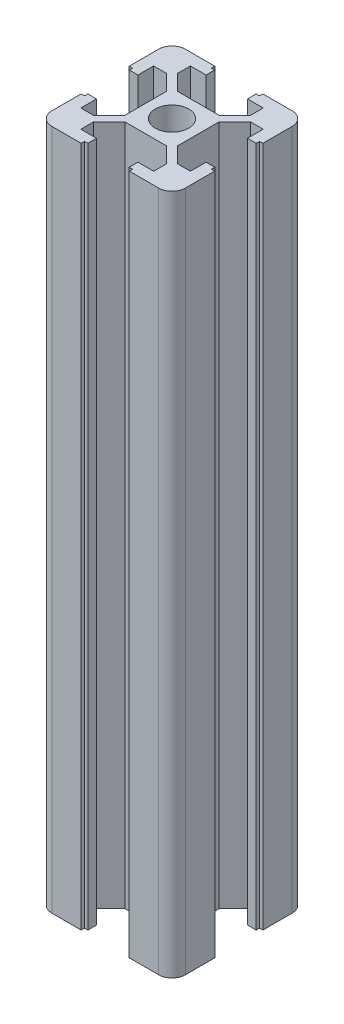
SolidWorks part; units mm, degrees
ref_plane "前视基准面" through (0, 0, 0) normal (0, 0, 1) x (1, 0, 0)
ref_plane "上视基准面" through (0, 0, 0) normal (0, 1, 0) x (1, 0, 0)
ref_plane "右视基准面" through (0, 0, 0) normal (1, 0, 0) x (0, 0, -1)
sketch "草图1" plane through (0, 0, 0) normal (0, 1, 0) x (1, 0, 0)
  line L0 (-6.2985, -5.45) -> (-3.9485, -3.1)
  line L1 (-5.45, -6.2985) -> (-3.1, -3.9485)
  line L2 (-6.2985, -5.45) -> (-8.2, -5.45)
  line L3 (-8.2, -5.45) -> (-8.2, -3.1)
  line L4 (-8.2, -3.1) -> (-10, -3.1)
  line L5 (-10, -3.1) -> (-10, -8)
  line L6 (-8, -10) -> (-3.1, -10)
  line L7 (-5.45, -6.2985) -> (-5.45, -8.2)
  line L8 (-5.45, -8.2) -> (-3.1, -8.2)
  line L9 (-3.1, -8.2) -> (-3.1, -10)
  line L10 (-3.9485, 0) -> (-3.9485, -3.1)
  line L11 (-3.1, -3.9485) -> (0, -3.9485)
  line L12 (-10, -3.6) -> (-9.5, -3.6)
  line L13 (-9.5, -3.6) -> (-9.5, -3.1)
  line L14 (-3.6, -10) -> (-3.6, -9.5)
  line L15 (-3.6, -9.5) -> (-3.1, -9.5)
  line L16 (-3.9485, 0) -> (-2.5, 0) construction
  line L17 (0, -2.5) -> (0, -3.9485) construction
  line L18 (-5.45, 6.2985) -> (-3.1, 3.9485)
  line L19 (-6.2985, 5.45) -> (-3.9485, 3.1)
  line L20 (-5.45, 6.2985) -> (-5.45, 8.2)
  line L21 (-5.45, 8.2) -> (-3.1, 8.2)
  line L22 (-3.1, 8.2) -> (-3.1, 10)
  line L23 (-3.1, 10) -> (-8, 10)
  line L24 (-10, 8) -> (-10, 3.1)
  line L25 (-6.2985, 5.45) -> (-8.2, 5.45)
  line L26 (-8.2, 5.45) -> (-8.2, 3.1)
  line L27 (-8.2, 3.1) -> (-10, 3.1)
  line L28 (-3.1, 3.9485) -> (0, 3.9485)
  line L29 (-3.9485, 3.1) -> (-3.9485, 0)
  line L30 (-3.6, 10) -> (-3.6, 9.5)
  line L31 (-3.6, 9.5) -> (-3.1, 9.5)
  line L32 (-10, 3.6) -> (-9.5, 3.6)
  line L33 (-9.5, 3.6) -> (-9.5, 3.1)
  line L34 (0, 3.9485) -> (0, 2.5) construction
  line L35 (-2.5, 0) -> (-3.9485, 0) construction
  line L36 (6.2985, 5.45) -> (3.9485, 3.1)
  line L37 (5.45, 6.2985) -> (3.1, 3.9485)
  line L38 (6.2985, 5.45) -> (8.2, 5.45)
  line L39 (8.2, 5.45) -> (8.2, 3.1)
  line L40 (8.2, 3.1) -> (10, 3.1)
  line L41 (10, 3.1) -> (10, 8)
  line L42 (8, 10) -> (3.1, 10)
  line L43 (5.45, 6.2985) -> (5.45, 8.2)
  line L44 (5.45, 8.2) -> (3.1, 8.2)
  line L45 (3.1, 8.2) -> (3.1, 10)
  line L46 (3.9485, 0) -> (3.9485, 3.1)
  line L47 (3.1, 3.9485) -> (0, 3.9485)
  line L48 (10, 3.6) -> (9.5, 3.6)
  line L49 (9.5, 3.6) -> (9.5, 3.1)
  line L50 (3.6, 10) -> (3.6, 9.5)
  line L51 (3.6, 9.5) -> (3.1, 9.5)
  line L52 (3.9485, 0) -> (2.5, 0) construction
  line L53 (0, 2.5) -> (0, 3.9485) construction
  line L54 (5.45, -6.2985) -> (3.1, -3.9485)
  line L55 (6.2985, -5.45) -> (3.9485, -3.1)
  line L56 (5.45, -6.2985) -> (5.45, -8.2)
  line L57 (5.45, -8.2) -> (3.1, -8.2)
  line L58 (3.1, -8.2) -> (3.1, -10)
  line L59 (3.1, -10) -> (8, -10)
  line L60 (10, -8) -> (10, -3.1)
  line L61 (6.2985, -5.45) -> (8.2, -5.45)
  line L62 (8.2, -5.45) -> (8.2, -3.1)
  line L63 (8.2, -3.1) -> (10, -3.1)
  line L64 (0, -3.9485) -> (3.1, -3.9485)
  line L65 (3.9485, -3.1) -> (3.9485, 0)
  line L66 (3.6, -10) -> (3.6, -9.5)
  line L67 (3.6, -9.5) -> (3.1, -9.5)
  line L68 (10, -3.6) -> (9.5, -3.6)
  line L69 (9.5, -3.6) -> (9.5, -3.1)
  line L70 (0, -3.9485) -> (0, -2.5) construction
  line L71 (2.5, 0) -> (3.9485, 0) construction
  line L72 (0, 3.9485) -> (-3.1, 3.9485) [skipped]
  circle A0 centre (0, 0) radius 2.5
  arc A1 (-10, -8) -> (-8, -10) centre (-8, -8) ccw
  arc A3 (-8, 10) -> (-10, 8) centre (-8, 8) ccw
  arc A5 (10, 8) -> (8, 10) centre (8, 8) ccw
  arc A7 (8, -10) -> (10, -8) centre (8, -8) ccw
  point P25 (-10, -10)
  point P98 (0, 0)
  dimension "D9" = 2
  dimension "D15" = 5
  dimension "D2" = 1.2
  dimension "D4" = 5.45
  dimension "D5" = 1.8
  dimension "D6" = 3.1
  dimension "D7" = 135
  dimension "D10" = 0.5
  dimension "D11" = 0.5
  dimension "D12" = 0.5
  dimension "D13" = 0.5
  dimension "D14" = 4
extrude "凸台-拉伸1" add sketch "草图1" along normal blind 102 contours L59 A7 L60 L68 L69 L63 L62 L61 L55 L65 L46 L36 L38 L39 L40 L49 L48 L41 A5 L42 L50 L51 L45 L44 L43 L37 L47 L28 L18 L20 L21 L22 L31 L30 L23 A3 L24 L32 L33 L27 L26 L25 L19 L29 L10 L0 L2 L3 L4 L13 L12
